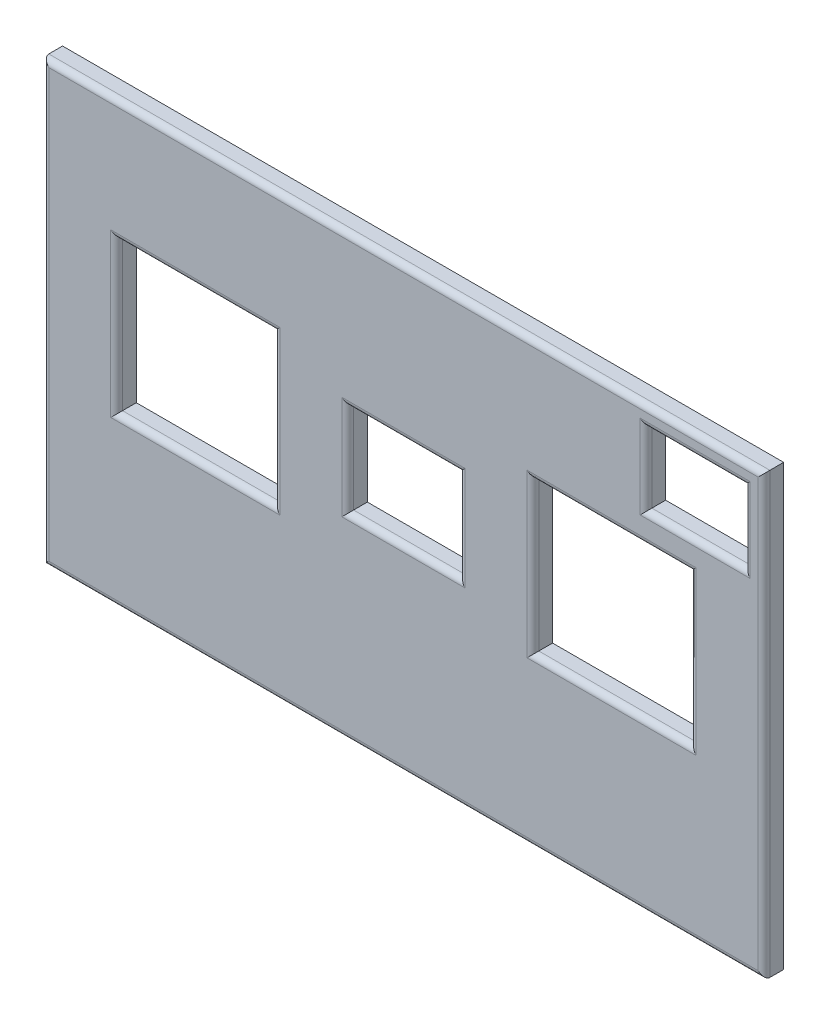
SolidWorks part; units mm, degrees
ref_plane "Front Plane" through (0, 0, 0) normal (0, 0, 1) x (1, 0, 0)
ref_plane "Top Plane" through (0, 0, 0) normal (0, 1, 0) x (1, 0, 0)
ref_plane "Right Plane" through (0, 0, 0) normal (1, 0, 0) x (0, 0, -1)
sketch "Sketch1" plane through (0, 0, 0) normal (0, 0, 1) x (1, 0, 0)
  line L1 (-55, -33.5) -> (55, -33.5)
  line L2 (-55, -33.5) -> (-55, 33.5)
  line L3 (-55, 33.5) -> (55, 33.5)
  line L4 (55, -33.5) -> (55, 33.5)
  line L5 (-55, -33.5) -> (55, 33.5) construction
  line L6 (-55, 33.5) -> (55, -33.5) construction
  point P0 (0, 0)
  dimension "D1" = 110
  dimension "D2" = 67
extrude "Boss-Extrude1" add sketch "Sketch1" along normal blind 3
sketch "Sketch2" plane through (0, 0, 3) normal (0, 0, 1) x (1, 0, 0)
  line L0 (-55, 33.5) -> (-55, -33.5) construction
  line L1 (-43.75, 15) -> (-19.75, 15)
  line L2 (-43.75, 15) -> (-43.75, -8)
  line L3 (-43.75, -8) -> (-19.75, -8)
  line L4 (-19.75, 15) -> (-19.75, -8)
  line L5 (-43.75, 15) -> (-19.75, -8) construction
  line L6 (-43.75, -8) -> (-19.75, 15) construction
  line L7 (-8.5, 10.5) -> (8.5, 10.5)
  line L8 (-8.5, 10.5) -> (-8.5, -3.5)
  line L9 (-8.5, -3.5) -> (8.5, -3.5)
  line L10 (8.5, 10.5) -> (8.5, -3.5)
  line L11 (-8.5, 10.5) -> (8.5, -3.5) construction
  line L12 (-8.5, -3.5) -> (8.5, 10.5) construction
  line L13 (19.75, 15) -> (43.75, 15)
  line L14 (19.75, 15) -> (19.75, -8)
  line L15 (19.75, -8) -> (43.75, -8)
  line L16 (43.75, 15) -> (43.75, -8)
  line L17 (19.75, 15) -> (43.75, -8) construction
  line L18 (19.75, -8) -> (43.75, 15) construction
  line L19 (55, 33.5) -> (-55, 33.5) construction
  line L20 (55, -33.5) -> (55, 33.5) construction
  line L21 (37, 30.5) -> (52, 30.5)
  line L22 (37, 30.5) -> (37, 19.5)
  line L23 (37, 19.5) -> (52, 19.5)
  line L24 (52, 30.5) -> (52, 19.5)
  line L25 (37, 30.5) -> (52, 19.5) construction
  line L26 (37, 19.5) -> (52, 30.5) construction
  point P0 (-31.75, 3.5)
  point P5 (0, 3.5)
  point P10 (31.75, 3.5)
  point P20 (44.5, 25)
  dimension "D1" = 23
  dimension "D2" = 24
  dimension "D3" = 14
  dimension "D4" = 17
  dimension "D5" = 23
  dimension "D6" = 24
  dimension "D7" = 11.25
  dimension "D8" = 11.25
  dimension "D9" = 11.25
  dimension "D10" = 18.5
  dimension "D11" = 11
  dimension "D12" = 15
  dimension "D13" = 3
  dimension "D14" = 3
extrude "Cut-Extrude1" cut sketch "Sketch2" against normal up to next
fillet "Fillet1" radius 0.9 20 edges at (-43.75, 3.5, 3) (-31.75, -8, 3) (-19.75, 3.5, 3) (-31.75, 15, 3) (0, -33.5, 3) (-55, 0, 3) (0, 33.5, 3) (55, 0, 3) (37, 25, 3) (44.5, 19.5, 3) (52, 25, 3) (44.5, 30.5, 3) (19.75, 3.5, 3) (31.75, -8, 3) (43.75, 3.5, 3) (31.75, 15, 3) (-8.5, 3.5, 3) (0, -3.5, 3) (8.5, 3.5, 3) (0, 10.5, 3)
